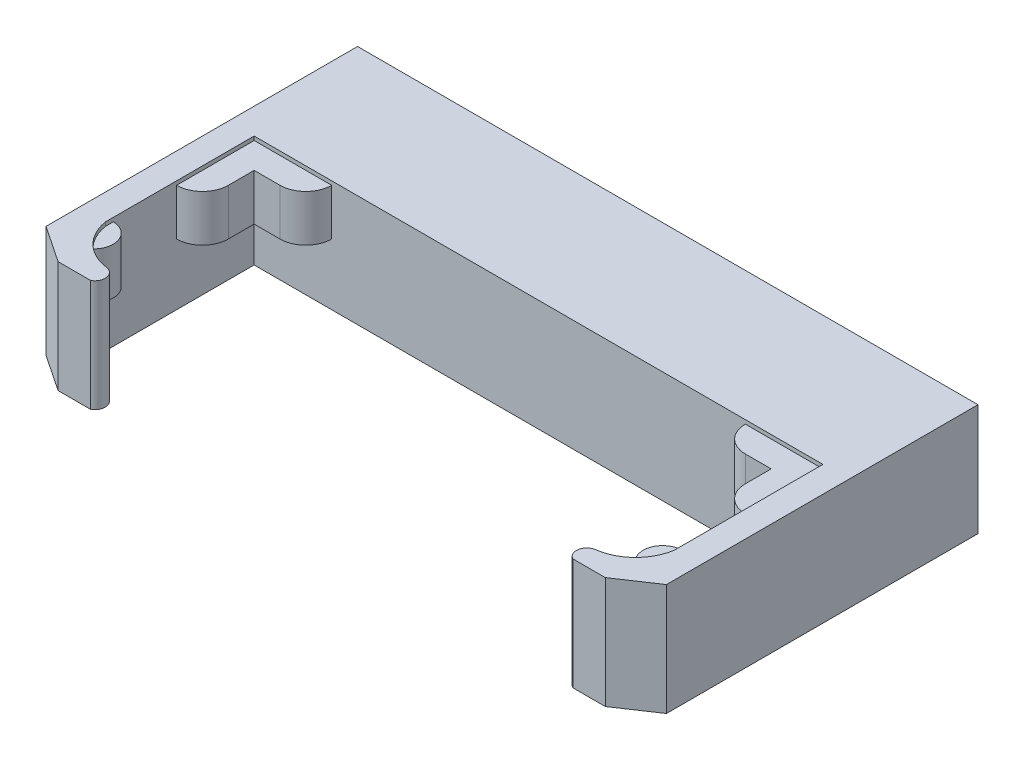
SolidWorks part; units mm, degrees
ref_plane "Front Plane" through (0, 0, 0) normal (0, 0, 1) x (1, 0, 0)
ref_plane "Top Plane" through (0, 0, 0) normal (0, 1, 0) x (1, 0, 0)
ref_plane "Right Plane" through (0, 0, 0) normal (1, 0, 0) x (0, 0, -1)
sketch "Sketch1" plane through (0, 0, 0) normal (0, 1, 0) x (1, 0, 0)
  line L0 (-110, 50) -> (-110, -7.5)
  line L1 (-120, 100) -> (120, 100)
  line L2 (-120, 100) -> (-120, 50)
  line L3 (-110, 50) -> (110, 50)
  line L4 (120, 100) -> (120, 50)
  line L6 (-120, -20.5095) -> (-120, 50)
  line L7 (120, 50) -> (120, -8.2)
  line L9 (110, -7.5) -> (110, 50)
  line L11 (-93.25, -30) -> (-105.831, -30)
  line L17 (120, -8.2) -> (105.831, -30)
  line L18 (105.831, -30) -> (93.25, -30)
  line L19 (-120, -20.5095) -> (-105.831, -30)
  arc A2 (-110, -7.5) -> (-94.5, -22.5368) centre (-92.222, -4.6815) ccw
  arc A3 (-110, -7.5) -> (-94.5, -22.5368) centre (-92.222, -4.6815) ccw construction
  arc A4 (-94.5, -22.5368) -> (-93.25, -30) centre (-95.1559, -26.4829) cw
  arc A5 (-93.25, -30) -> (-94.5, -22.5368) centre (-95.1559, -26.4829) ccw construction
  arc A6 (93.25, -30) -> (94.5, -22.5368) centre (95.1559, -26.4829) cw
  arc A7 (94.5, -22.5368) -> (93.25, -30) centre (95.1559, -26.4829) ccw construction
  arc A8 (94.5, -22.5368) -> (110, -7.5) centre (92.222, -4.6815) ccw
  arc A9 (94.5, -22.5368) -> (110, -7.5) centre (92.222, -4.6815) ccw construction
extrude "Boss-Extrude1" add sketch "Sketch1" against normal up to vertex (19.2 mm away) and the other way up to vertex (24 mm away)
sketch "Sketch4" plane through (0, 24, 0) normal (0, 1, 0) x (1, 0, 0)
  line L0 (0, 100) -> (0, 49.2978) construction
  line L1 (-120, 100) -> (120, 100) construction
  line L2 (0, -100) -> (0, 70) construction
  line L3 (-120, 100) -> (-120, 50) construction
  line L4 (-97, 94) -> (97, 94)
  line L5 (-97, 94) -> (-97, 56)
  line L6 (-97, 56) -> (97, 56)
  line L7 (97, 94) -> (97, 56)
  line L8 (-120, 50) -> (120, 50) construction
  line L9 (-97, 75) -> (97, 75) construction
  line L10 (120, 100) -> (120, 50) construction
  point P6 (0, 78.4712)
  dimension "D1" = 23
  dimension "D2" = 6
  dimension "D3" = 6
  dimension "D4" = 23
extrude "Cut-Extrude1" cut sketch "Sketch4" against normal offset from surface (41.2 mm away) 2 up to face at (0, -19.2, -6.2103)
sketch "Sketch5" plane through (-97, 0, 0) normal (1, 0, 0) x (0, 0, -1)
  line L0 (79.5025, 11.5) -> (88.035, 11.5)
  line L1 (61.965, -11.5) -> (70.4975, -11.5)
  line L2 (61.965, -11.5) -> (61.965, 11.5)
  line L3 (61.965, 11.5) -> (70.4975, 11.5)
  line L4 (88.035, -11.5) -> (88.035, 11.5)
  line L5 (61.965, -11.5) -> (88.035, 11.5) construction
  line L6 (61.965, 11.5) -> (88.035, -11.5) construction
  line L7 (79.5025, -11.5) -> (88.035, -11.5)
  arc A0 (79.5025, 11.5) -> (70.4975, 11.5) centre (75, 0) ccw
  arc A1 (70.4975, -11.5) -> (79.5025, -11.5) centre (75, 0) ccw
  point P0 (75, 0)
  dimension "D3" = 24.7
  dimension "D1" = 23
  dimension "D2" = 26.07
extrude "Cut-Extrude2" cut sketch "Sketch5" against normal blind 21
sketch "Sketch7" plane through (-118, 0, 0) normal (1, 0, 0) x (0, 0, -1)
  circle A0 centre (75, 0) radius 8
  dimension "D1" = 16
extrude "Cut-Extrude3" cut sketch "Sketch7" against normal blind 21
mirror "Mirror1" about plane through (0, 0, 0) normal (1, 0, 0) of "Cut-Extrude3", "Cut-Extrude2"
ref_plane "Bottom of Top Cf" through (0, 22.5, 0) normal (0, 1, 0) x (1, 0, 0)
ref_plane "Top of Bottom Cf" through (0, 4.5, 0) normal (0, 1, 0) x (1, 0, 0)
ref_plane "Plane1" through (0, 3, 0) normal (0, 1, 0) x (1, 0, 0)
sketch "Sketch12" plane through (0, 3, 0) normal (0, 1, 0) x (1, 0, 0)
mirror "Mirror4" about plane through (0, 0, 0) normal (1, 0, 0) of "Boss-Extrude1"
sketch "Sketch8" plane through (0, 4.5, 0) normal (0, 1, 0) x (1, 0, 0)
  line L0 (-110, 50) -> (-110, -30) construction
  line L1 (-90, 50) -> (-110, 50)
  line L2 (-110, 50) -> (-110, 30)
  line L3 (-110, 40) -> (-100, 40) construction
  line L4 (-100, 50) -> (-100, 40) construction
  line L5 (-110, -4.5) -> (-110, -19.5)
  line L6 (-100, 40) -> (-100, 30)
  line L7 (-100, 40) -> (-90, 40)
  line L8 (-110, 30) -> (-100, 30) construction
  line L9 (-110, 20) -> (-110, 30)
  line L10 (-90, 50) -> (-80, 50)
  line L11 (-90, 40) -> (-90, 50) construction
  arc A0 (-110, -19.5) -> (-110, -4.5) centre (-110, -12) ccw
  arc A4 (-90, 40) -> (-80, 50) centre (-90, 50) ccw
  arc A5 (-110, 20) -> (-100, 30) centre (-110, 30) ccw
  dimension "D1" = 15
  dimension "D2" = 18
  dimension "D3" = 10
  dimension "D4" = 10
  dimension "D5" = 10
  dimension "D6" = 10
extrude "Boss-Extrude3" add sketch "Sketch8" along normal up to surface (18 mm away) separate body
mirror "Mirror2" about plane through (0, 0, 0) normal (1, 0, 0) of "Boss-Extrude3"
sketch "Sketch11" plane through (-120, 0, 0) normal (-1, 0, 0) x (0, 0, 1)
  line L1 (24.75, 4.5) -> (30, 4.5)
  line L2 (24.75, 4.5) -> (24.75, 6)
  line L3 (24.75, 6) -> (30, 6)
  line L4 (30, 4.5) -> (30, 6)
  dimension "D1" = 1.5
